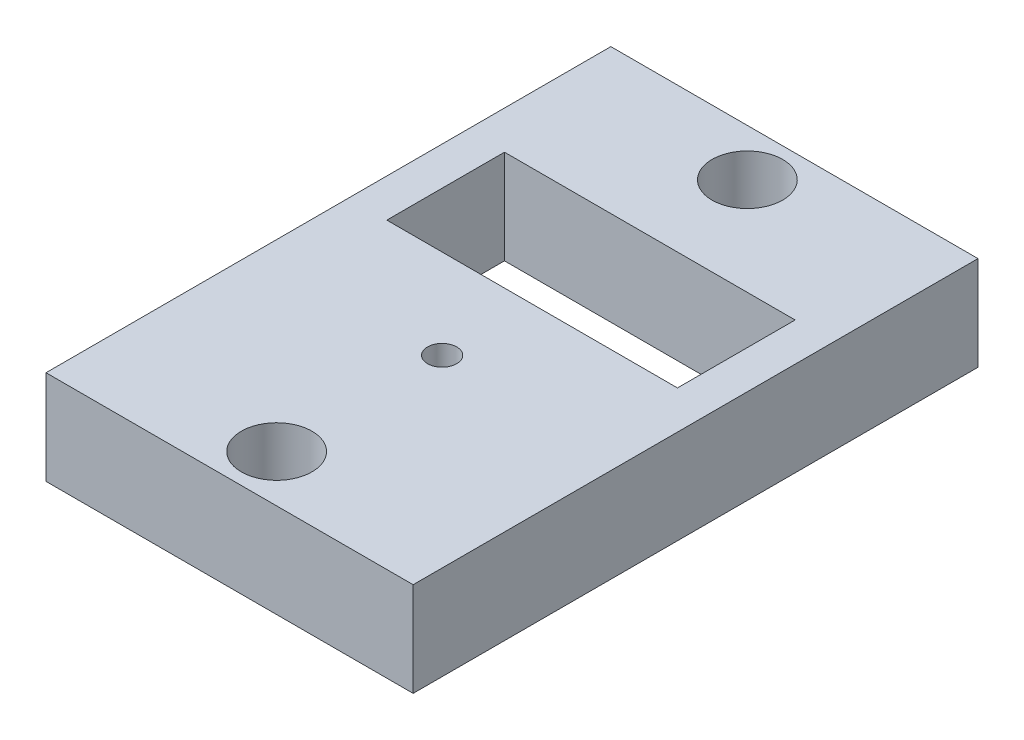
SolidWorks part; units mm, degrees
material "Plain Carbon Steel"
ref_plane "Front Plane" through (0, 0, 0) normal (0, 0, 1) x (1, 0, 0)
ref_plane "Top Plane" through (0, 0, 0) normal (0, 1, 0) x (1, 0, 0)
ref_plane "Right Plane" through (0, 0, 0) normal (1, 0, 0) x (0, 0, -1)
sketch "Sketch1" plane through (0, 0, 0) normal (0, 1, 0) x (1, 0, 0)
  line L5 (-78, -60) -> (0, -60)
  line L6 (-78, -60) -> (-78, 60)
  line L7 (-78, 60) -> (0, 60)
  line L8 (0, -60) -> (0, 60)
  line L9 (-39, 29.28) -> (-39, 4.28) construction
  line L10 (-8.125, 29.28) -> (-69.875, 29.28) construction
  line L11 (-8.125, 4.28) -> (-69.875, 4.28) construction
  point P4 (0, 0)
  dimension "D1" = 120
extrude "Boss-Extrude1" add sketch "Sketch1" along normal mid plane 20
sketch "Sketch2" plane through (0, 10, 0) normal (0, 1, 0) x (1, 0, 0)
  line L1 (-69.875, 29.28) -> (-8.125, 29.28)
  line L2 (-69.875, 29.28) -> (-69.875, 4.28)
  line L3 (-69.875, 4.28) -> (-8.125, 4.28)
  line L4 (-8.125, 29.28) -> (-8.125, 4.28)
extrude "Cut-Extrude1" cut sketch "Sketch2" against normal up to next
sketch "Sketch3" plane through (0, 10, 0) normal (0, 1, 0) x (1, 0, 0)
  line L0 (-39, 60) -> (-39, -60) construction
  line L1 (0, 60) -> (-78, 60) construction
  line L2 (-78, -60) -> (0, -60) construction
  circle A0 centre (-39, 50) radius 7.5
  circle A1 centre (-39, -50) radius 7.5
  dimension "D1" = 15
  dimension "D2" = 10
  dimension "D3" = 10
extrude "Cut-Extrude2" cut sketch "Sketch3" against normal up to next
sketch "Sketch5" plane through (0, 10, 0) normal (0, 1, 0) x (1, 0, 0)
  circle A0 centre (-39.125, -14.72) radius 3.1 construction
  circle A1 centre (-39.125, -14.72) radius 3.1
extrude "Cut-Extrude3" cut sketch "Sketch5" against normal up to next
